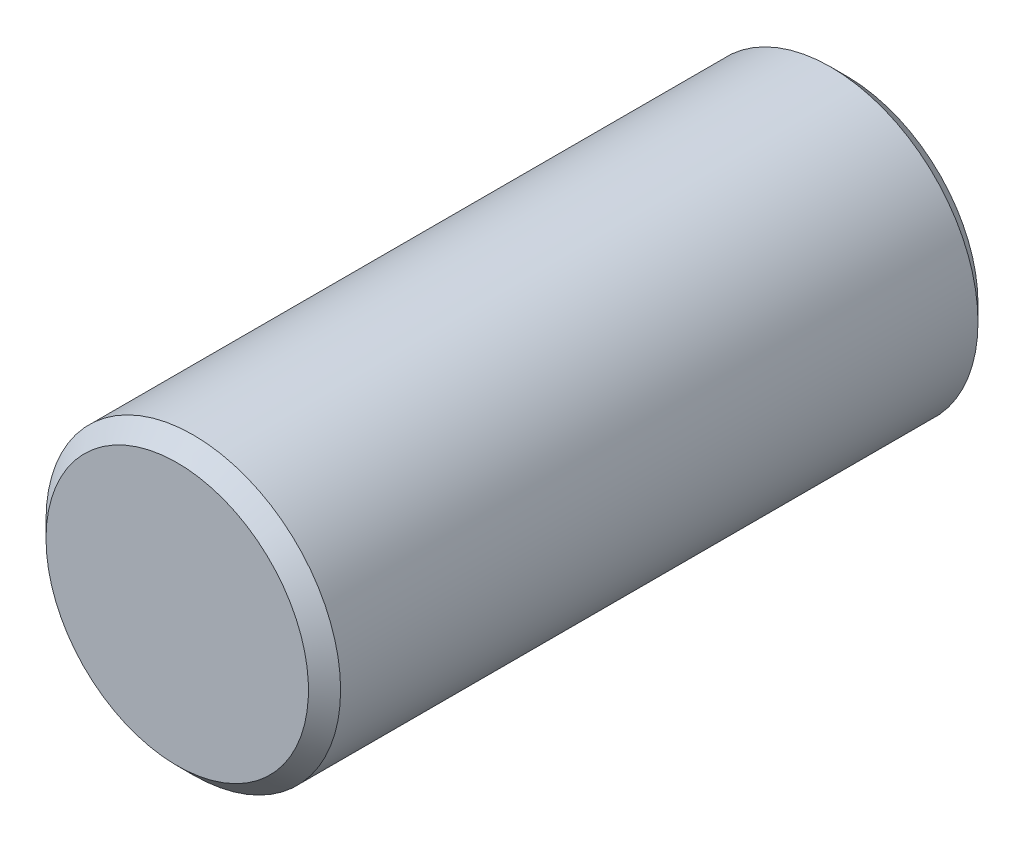
SolidWorks part; units mm, degrees
material "45"
ref_plane "前视基准面" through (0, 0, 0) normal (0, 0, 1) x (1, 0, 0)
ref_plane "上视基准面" through (0, 0, 0) normal (0, 1, 0) x (1, 0, 0)
ref_plane "右视基准面" through (0, 0, 0) normal (1, 0, 0) x (0, 0, -1)
sketch "草图1" plane through (0, 0, 0) normal (0, 0, 1) x (1, 0, 0)
  circle A0 centre (0, 0) radius 27.5
  dimension "D1" = 55
extrude "凸台-拉伸1" add sketch "草图1" along normal mid plane 125
chamfer "倒角1" distance 3 angle 45 2 edges at (27.5, 0, -62.5) (27.5, 0, 62.5)
